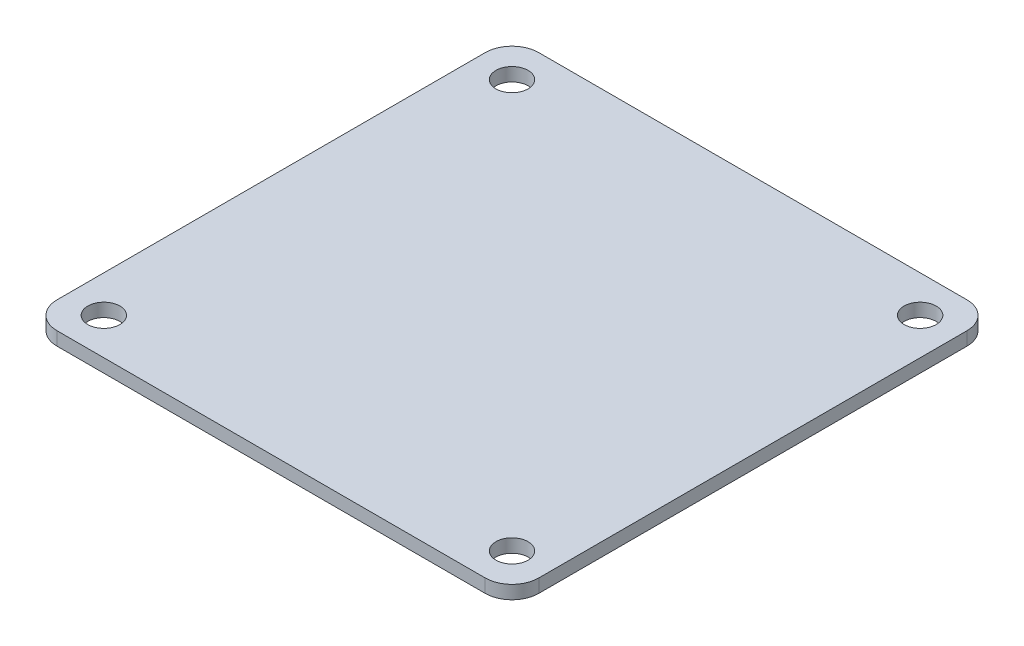
SolidWorks part; units mm, degrees
ref_plane "Front Plane" through (0, 0, 0) normal (0, 0, 1) x (1, 0, 0)
ref_plane "Top Plane" through (0, 0, 0) normal (0, 1, 0) x (1, 0, 0)
ref_plane "Right Plane" through (0, 0, 0) normal (1, 0, 0) x (0, 0, -1)
sketch "Sketch1" plane through (0, 0, 0) normal (0, 1, 0) x (1, 0, 0)
  line L1 (18, 18) -> (-18, 18)
  line L2 (18, 18) -> (18, -18)
  line L3 (18, -18) -> (-18, -18)
  line L4 (-18, 18) -> (-18, -18)
  line L5 (18, 18) -> (-18, -18) construction
  line L6 (18, -18) -> (-18, 18) construction
  point P0 (0, 0)
  dimension "D1" = 36
extrude "Boss-Extrude1" add sketch "Sketch1" along normal blind 1
hole_wizard "M2 Clearance Hole1" positions "Sketch3" profile "Sketch2" hole size "M2" standard "ANSI Metric" end condition through all
sketch "Sketch3" plane through (0, 1, 0) normal (0, 1, 0) x (1, 0, 0)
  line L0 (0, 0) -> (0, -50000) construction
  line L1 (0, 0) -> (-50000, 0) construction
  point P0 (-15.25, 15.25)
  point P2 (15.25, 15.25)
  point P4 (15.25, -15.25)
  point P6 (-15.25, -15.25)
  dimension "D1" = 30.5
  dimension "D2" = 30.5
sketch "Sketch2" plane through (-15.25, 1, -15.25) normal (1, 0, 0) x (0, 0, 1)
  line L0 (0, 0) -> (0, 1)
  line L1 (0, 1) -> (1.2, 1)
  line L2 (1.2, 1) -> (1.2, 0)
  line L5 (1.2, 0) -> (0, 0)
  line L11 (0, -6.35) -> (0, 107.95) construction
  dimension "Thru Hole Dia." = 2.4
  dimension "Thru Hole Depth" = 1
fillet "Fillet1" radius 2 4 edges at (18, 0.5, -18) (18, 0.5, 18) (-18, 0.5, 18) (-18, 0.5, -18)
